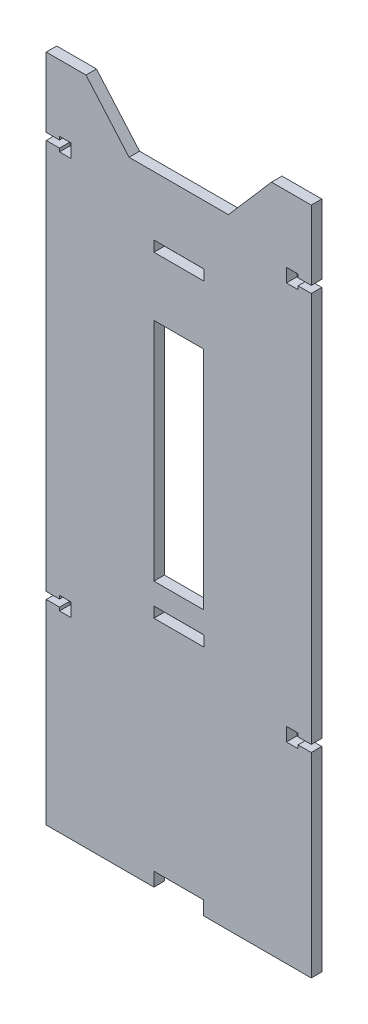
SolidWorks part; units mm, degrees
ref_plane "Front Plane" through (0, 0, 0) normal (0, 0, 1) x (1, 0, 0)
ref_plane "Top Plane" through (0, 0, 0) normal (0, 1, 0) x (1, 0, 0)
ref_plane "Right Plane" through (0, 0, 0) normal (1, 0, 0) x (0, 0, -1)
other "Center of Mass"
sketch "Sketch1" plane through (0, 0, 0) normal (0, 0, 1) x (1, 0, 0)
  line L1 (-50, 345) -> (30, 345)
  line L2 (-50, 345) -> (-50, -40)
  line L3 (-50, -40) -> (30, -40)
  line L4 (30, 345) -> (30, -40)
  dimension "D1" = 385
  dimension "D2" = 80
  dimension "D3" = 30
  dimension "D4" = 40
extrude "Boss-Extrude1" add sketch "Sketch1" against normal blind 3.175
sketch "Sketch2" plane through (0, 0, 0) normal (0, 0, 1) x (1, 0, 0)
  line L0 (-50, 345) -> (-50, -40) construction
  line L1 (-50, 330) -> (-53.5, 330)
  line L2 (-50, 330) -> (-50, 315)
  line L3 (-50, 315) -> (-53.5, 315)
  line L4 (-53.5, 330) -> (-53.5, 315)
  line L5 (30, 345) -> (-50, 345) construction
  line L7 (-50, 82.5) -> (-53.5, 82.5)
  line L8 (-50, 82.5) -> (-50, 67.5)
  line L9 (-50, 67.5) -> (-53.5, 67.5)
  line L10 (-53.5, 82.5) -> (-53.5, 67.5)
  line L11 (-50, -10) -> (-53.5, -10)
  line L12 (-50, -10) -> (-50, -25)
  line L13 (-50, -25) -> (-53.5, -25)
  line L14 (-53.5, -10) -> (-53.5, -25)
  dimension "D1" = 15
  dimension "D2" = 15
  dimension "D3" = 3.5
  dimension "D4" = 0
  dimension "D5" = 67.5
  dimension "D6" = 15
  dimension "D7" = 15
  dimension "D8" = 15
  dimension "D9" = 3.5
sketch "Sketch6" plane through (0, 0, 0) normal (0, 0, 1) x (1, 0, 0)
  line L0 (-50, 336.05) -> (-46, 336.05)
  line L1 (-50, 345) -> (-50, -40) construction
  line L2 (-46, 336.05) -> (-46, 337.05)
  line L3 (-46, 337.05) -> (-42.5, 337.05)
  line L4 (-42.5, 337.05) -> (-42.5, 332.95)
  line L5 (-42.5, 332.95) -> (-46, 332.95)
  line L6 (-46, 332.95) -> (-46, 333.95)
  line L7 (-46, 333.95) -> (-50, 333.95)
  line L8 (-50, 333.95) -> (-50, 336.05)
  point P4 (-50, 335)
  dimension "D1" = 2.1
  dimension "D2" = 4.1
  dimension "D3" = 2.05
  dimension "D4" = 7.5
  dimension "D5" = 3.5
  dimension "D6" = 10
extrude "Cut-Extrude1" cut sketch "Sketch6" against normal blind 3.175
pattern_linear "LPattern1" count 2 spacing 60 along (0, -1, 0) of "Cut-Extrude1"
ref_plane "Plane1" through (-10, 0, 0) normal (-1, 0, 0) x (0, 0, 1)
pattern_linear "LPattern2" count 2 spacing 120 along (0, -1, 0) of "Cut-Extrude1"
pattern_linear "LPattern3" count 2 spacing 195 along (0, -1, 0) of "Cut-Extrude1"
pattern_linear "LPattern6" count 2 spacing 315 along (0, -1, 0) of "Cut-Extrude1"
mirror "Mirror2" about plane through (-10, 0, 0) normal (-1, 0, 0) of "LPattern6", "Cut-Extrude1", "LPattern3", "LPattern2", "LPattern1"
sketch "Sketch7" plane through (0, 0, 0) normal (0, 0, 1) x (1, 0, 0)
  line L0 (30, 345) -> (-50, 345) construction
  line L1 (-17.5, 345) -> (-2.5, 345)
  line L2 (-17.5, 345) -> (-17.5, 340.825)
  line L3 (-17.5, 340.825) -> (-2.5, 340.825)
  line L4 (-2.5, 345) -> (-2.5, 340.825)
  line L5 (-50, -40) -> (30, -40) construction
  line L6 (-17.5, -40) -> (-2.5, -40)
  line L7 (-17.5, -40) -> (-17.5, -35.825)
  line L8 (-17.5, -35.825) -> (-2.5, -35.825)
  line L9 (-2.5, -40) -> (-2.5, -35.825)
  line L10 (-10, 1.7462) -> (-10, -1.7463) construction
  point P6 (-10, 345)
  point P7 (-10, -35.825)
  dimension "D1" = 15
  dimension "D2" = 4.175
  dimension "D4" = 4.175
  dimension "D5" = 15
extrude "Cut-Extrude2" cut sketch "Sketch7" against normal blind 10
sketch "Sketch8" plane through (0, 0, 0) normal (0, 0, 1) x (1, 0, 0)
  line L0 (1.7463, 0) -> (-1.7463, 0) construction
  line L1 (-17.5, 38.175) -> (-2.5, 38.175)
  line L2 (-17.5, 38.175) -> (-17.5, 35)
  line L3 (-17.5, 35) -> (-2.5, 35)
  line L4 (-2.5, 38.175) -> (-2.5, 35)
  line L5 (-2.5, -35.825) -> (-17.5, -35.825) construction
  point P6 (-10, 38.175)
  point P9 (-10, -35.825)
  dimension "D1" = 15
  dimension "D2" = 3.175
  dimension "D3" = 35
  dimension "D4" = 0
extrude "Cut-Extrude3" cut sketch "Sketch8" against normal blind 10
sketch "Sketch9" plane through (0, 0, 0) normal (0, 0, 1) x (1, 0, 0)
  line L0 (-17.5, 38.175) -> (-17.5, 35) construction
  line L1 (-17.5, 129.175) -> (-2.4, 129.175)
  line L2 (-17.5, 129.175) -> (-17.5, 125.975)
  line L3 (-17.5, 125.975) -> (-2.4, 125.975)
  line L4 (-2.4, 129.175) -> (-2.4, 125.975)
  line L6 (-2.5, 38.175) -> (-17.5, 38.175) construction
  dimension "D1" = 3.2
  dimension "D2" = 15.1
  dimension "D3" = 0
  dimension "D4" = 91
extrude "Cut-Extrude4" cut sketch "Sketch9" against normal through all
sketch "Sketch11" plane through (0, 0, 0) normal (0, 0, 1) x (1, 0, 0)
  line L0 (-17.5, 340.825) -> (-2.5, 340.825) construction
  line L1 (14, 325.825) -> (14, 267.825) construction
  line L2 (14, 267.825) -> (-34, 267.825) construction
  line L3 (-34, 267.825) -> (-34, 325.825) construction
  line L4 (-34, 325.825) -> (14, 325.825) construction
  line L5 (-10, 1.7462) -> (-10, -1.7463) construction
  circle A0 centre (-34, 325.825) radius 1.55
  circle A1 centre (-34, 267.825) radius 1.55
  circle A2 centre (14, 325.825) radius 1.55
  circle A3 centre (14, 267.825) radius 1.55
  point P11 (-10, 325.825)
  dimension "D1" = 3.1
  dimension "D3" = 15
  dimension "D4" = 3.1
  dimension "D5" = 3.1
  dimension "D6" = 3.1
  dimension "D7" = 58
  dimension "D11" = 58
  dimension "D10" = 48
extrude "Cut-Extrude6" cut sketch "Sketch11" against normal through all
sketch "Sketch12" plane through (0, 0, 0) normal (0, 0, 1) x (1, 0, 0)
  line L0 (-2, 286.825) -> (-2, 314.825)
  line L1 (2, 314.825) -> (2, 286.825)
  line L2 (-17.5, 340.825) -> (-2.5, 340.825) construction
  arc A0 (-2, 314.825) -> (2, 314.825) centre (0, 314.825) cw
  arc A1 (-2, 286.825) -> (2, 286.825) centre (0, 286.825) ccw
  dimension "D1" = 2
  dimension "D2" = 28
  dimension "D3" = 0
  dimension "D4" = 26
extrude "Cut-Extrude7" cut sketch "Sketch12" against normal blind 10
pattern_linear "LPattern4" count 3 spacing 7 along (1, 0, 0) of "Cut-Extrude7"
mirror "Mirror4" about plane through (-10, 0, 0) normal (-1, 0, 0) of "LPattern4", "Cut-Extrude7"
sketch "Sketch14" plane through (0, 0, 0) normal (0, 0, 1) x (1, 0, 0)
  line L0 (-17.5, 340.825) -> (-2.5, 340.825) construction
  line L1 (-10, 1.7462) -> (-10, -1.7463) construction
  circle A0 centre (-10, 327.825) radius 1.55
  dimension "D1" = 3.1
  dimension "D2" = 13
extrude "Cut-Extrude9" cut sketch "Sketch14" against normal through all
pattern_linear "LPattern5" count 2 spacing 135 along (0, -1, 0) of "LPattern4", "Mirror4", "Cut-Extrude7"
sketch "Sketch15" plane through (0, 0, 0) normal (0, 0, 1) x (1, 0, 0)
  line L0 (-10, 1.7462) -> (-10, -1.7463) construction
  line L1 (-38, 240) -> (18, 240)
  line L2 (-42, 236) -> (-42, 229)
  line L3 (-38, 225) -> (18, 225)
  line L4 (22, 236) -> (22, 229)
  line L5 (-42, 240) -> (22, 225) construction
  line L6 (-42, 225) -> (22, 240) construction
  line L7 (-50, 273.95) -> (-50, 216.05) construction
  line L8 (30, 345) -> (-2.5, 345) construction
  arc A0 (18, 240) -> (22, 236) centre (18, 236) cw
  arc A1 (22, 229) -> (18, 225) centre (18, 229) cw
  arc A2 (-38, 225) -> (-42, 229) centre (-38, 229) cw
  arc A3 (-42, 236) -> (-38, 240) centre (-38, 236) cw
  point P0 (-10, 232.5)
  dimension "D4" = 4
  dimension "D1" = 15
  dimension "D2" = 8
  dimension "D3" = 105
extrude "Cut-Extrude10" cut sketch "Sketch15" against normal through all
pattern_linear "LPattern7" count 2 spacing 60 along (0, 1, 0) of "Cut-Extrude4"
sketch "Sketch17" plane through (0, 0, 0) normal (0, 0, 1) x (1, 0, 0)
  line L0 (-2.5, 35) -> (-2.5, 38.175) construction
  line L1 (-17.5, 38.175) -> (-2.5, 38.175)
  line L2 (-17.5, 38.175) -> (-17.5, 108.175)
  line L3 (-17.5, 108.175) -> (-2.5, 108.175)
  line L4 (-2.5, 38.175) -> (-2.5, 108.175)
  dimension "D1" = 70
extrude "Cut-Extrude11" cut sketch "Sketch17" against normal through all both and the other way through all
sketch "Sketch18" plane through (0, 0, 0) normal (0, 0, 1) x (1, 0, 0)
  line L0 (-2.5, 35) -> (-2.5, 108.175) construction
  line L1 (-17.5, 35) -> (-2.5, 35)
  line L2 (-17.5, 35) -> (-17.5, 40)
  line L3 (-17.5, 40) -> (-2.5, 40)
  line L4 (-2.5, 35) -> (-2.5, 40)
  dimension "D1" = 5
extrude "Boss-Extrude3" add sketch "Sketch18" against normal up to surface (3.175 mm away) up to face at (-9.95, 187.575, -3.175)
sketch "Sketch19" plane through (0, 0, 0) normal (0, 0, 1) x (1, 0, 0)
  line L0 (-17.5, 108.175) -> (-17.5, 40) construction
  line L1 (-17.5, 33.5) -> (-2.4, 33.5)
  line L2 (-17.5, 33.5) -> (-17.5, 30.3)
  line L3 (-17.5, 30.3) -> (-2.4, 30.3)
  line L4 (-2.4, 33.5) -> (-2.4, 30.3)
  line L5 (-2.5, 40) -> (-17.5, 40) construction
  dimension "D1" = 3.2
  dimension "D2" = 15.1
  dimension "D3" = 6.5
extrude "Cut-Extrude12" cut sketch "Sketch19" against normal through all
sketch "Sketch20" plane through (0, 0, 0) normal (0, 0, 1) x (1, 0, 0)
  line L0 (-42.5, 142.05) -> (-46, 142.05) construction
  line L1 (-77.3863, 358.6421) -> (41.9189, 358.6421)
  line L2 (-77.3863, 358.6421) -> (-77.3863, 147.05)
  line L3 (-77.3863, 147.05) -> (41.9189, 147.05)
  line L4 (41.9189, 358.6421) -> (41.9189, 147.05)
  dimension "D1" = 5
extrude "Cut-Extrude13" cut sketch "Sketch20" against normal through all both and the other way through all
sketch "Sketch22" plane through (0, 0, 0) normal (0, 0, 1) x (1, 0, 0)
  line L0 (-50, 147.05) -> (-50, 162.05)
  line L1 (-50, 162.05) -> (-38, 162.05)
  line L2 (-38, 162.05) -> (-25, 147.05)
  line L3 (-50, 147.05) -> (30, 147.05) construction
  line L4 (-50, 147.05) -> (-25, 147.05)
  dimension "D1" = 15
  dimension "D2" = 12
  dimension "D3" = 25
extrude "Boss-Extrude4" add sketch "Sketch22" against normal up to surface (3.175 mm away) up to face at (-9.95, 31.9, -3.175)
mirror "Mirror5" about plane through (-10, 0, 0) normal (-1, 0, 0) of "Boss-Extrude4"
sketch "Sketch24" plane through (0, 0, -3.175) normal (0, 0, -1) x (-1, 0, 0)
  line L0 (-20.7823, 0.8517) -> (40.7823, 0.8517) construction
  line L1 (10, -1.7463) -> (10, 1.7462) construction
  text T0 "<b>UW BADGER LAB</b>" font "Century Gothic" height in points 20
  point P2 (10, 0.8517)
extrude "Cut-Extrude15" cut sketch "Sketch24" against normal blind 0.5
